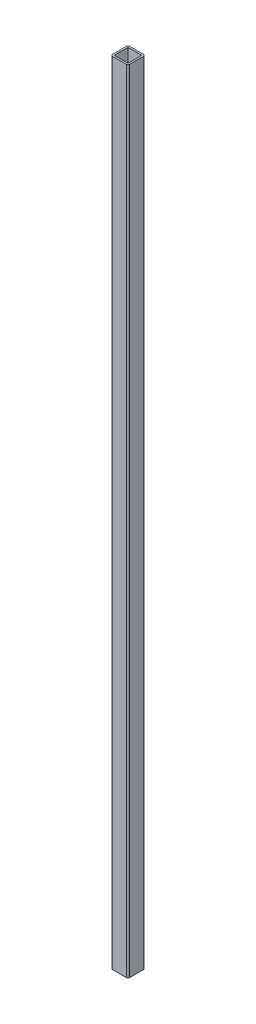
SolidWorks part; units mm, degrees
ref_plane "Front Plane" through (0, 0, 0) normal (0, 0, 1) x (1, 0, 0)
ref_plane "Top Plane" through (0, 0, 0) normal (0, 1, 0) x (1, 0, 0)
ref_plane "Right Plane" through (0, 0, 0) normal (1, 0, 0) x (0, 0, -1)
sketch "Sketch4" plane through (0, 0, 0) normal (0, 1, 0) x (1, 0, 0)
  line L0 (10.16, 10.16) -> (10.16, -10.16)
  line L1 (12.7, 12.7) -> (-12.7, 12.7)
  line L2 (12.7, 12.7) -> (12.7, -12.7)
  line L3 (12.7, -12.7) -> (-12.7, -12.7)
  line L4 (-12.7, 12.7) -> (-12.7, -12.7)
  line L5 (10.16, -10.16) -> (-10.16, -10.16)
  line L6 (-10.16, 10.16) -> (-10.16, -10.16)
  line L7 (10.16, 10.16) -> (-10.16, 10.16)
  point P0 (0, 0)
  dimension "D1" = 25.4
  dimension "D2" = 25.4
  dimension "D3" = 2.54
extrude "Boss-Extrude6" add sketch "Sketch4" along normal blind 1168.4 contours L4 L3 L2 L1
shell "Shell1" thickness 2.54
fillet "Fillet1" radius 2.54 4 edges at (-12.7, 584.2, 12.7) (12.7, 584.2, 12.7) (12.7, 584.2, -12.7) (-12.7, 584.2, -12.7)
